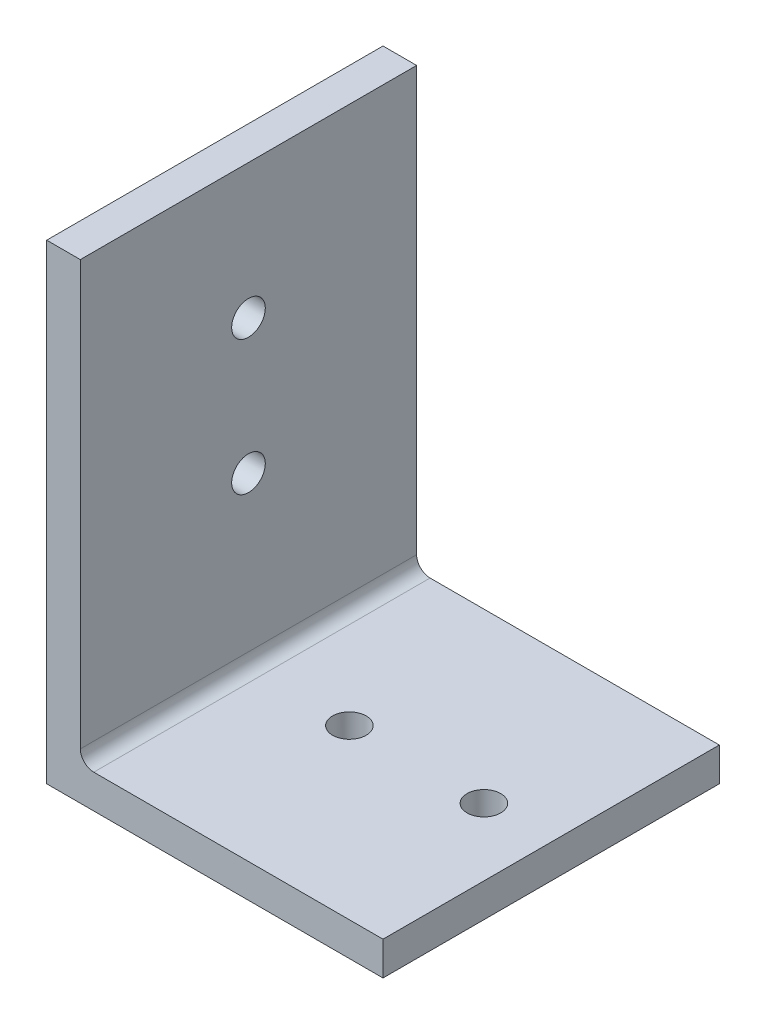
SolidWorks part; units mm, degrees
material "1023 Carbon Steel Sheet (SS)"
ref_plane "Front Plane" through (0, 0, 0) normal (0, 0, 1) x (1, 0, 0)
ref_plane "Top Plane" through (0, 0, 0) normal (0, 1, 0) x (1, 0, 0)
ref_plane "Right Plane" through (0, 0, 0) normal (1, 0, 0) x (0, 0, -1)
sketch "Sketch1" plane through (0, 0, 0) normal (0, 0, 1) x (1, 0, 0)
  line L0 (0, 0) -> (0, 88.9)
  line L1 (0, 88.9) -> (6.35, 88.9)
  line L2 (6.35, 88.9) -> (6.35, 6.35)
  line L3 (6.35, 6.35) -> (63.5, 6.35)
  line L4 (63.5, 6.35) -> (63.5, 0)
  line L5 (63.5, 0) -> (0, 0)
  dimension "D1" = 6.35
  dimension "D2" = 6.35
  dimension "D3" = 88.9
  dimension "D4" = 63.5
extrude "Boss-Extrude2" add sketch "Sketch1" along normal mid plane 63.5
sketch "Sketch2" plane through (0, 0, 0) normal (-1, 0, 0) x (0, 0, 1)
  line L0 (31.75, 88.9) -> (-31.75, 88.9) construction
  circle A0 centre (0, 63.5) radius 3.175
  circle A1 centre (0, 38.1) radius 3.175
  point P4 (0, 0)
  dimension "D1" = 6.35
  dimension "D2" = 25.4
  dimension "D3" = 25.4
extrude "Cut-Extrude1" cut sketch "Sketch2" against normal up to next
sketch "Sketch3" plane through (0, 0, 0) normal (0, -1, 0) x (1, 0, 0)
  line L0 (63.5, 31.75) -> (63.5, -31.75) construction
  circle A0 centre (25.4, 0) radius 3.175
  circle A1 centre (50.8, 0) radius 3.175
  point P4 (0, 0)
  point P5 (0, 0)
  dimension "D1" = 6.35
  dimension "D2" = 12.7
  dimension "D3" = 25.4
extrude "Cut-Extrude2" cut sketch "Sketch3" against normal up to next
fillet "Fillet2" radius 2.54 1 edges at (6.35, 6.35, 0)
